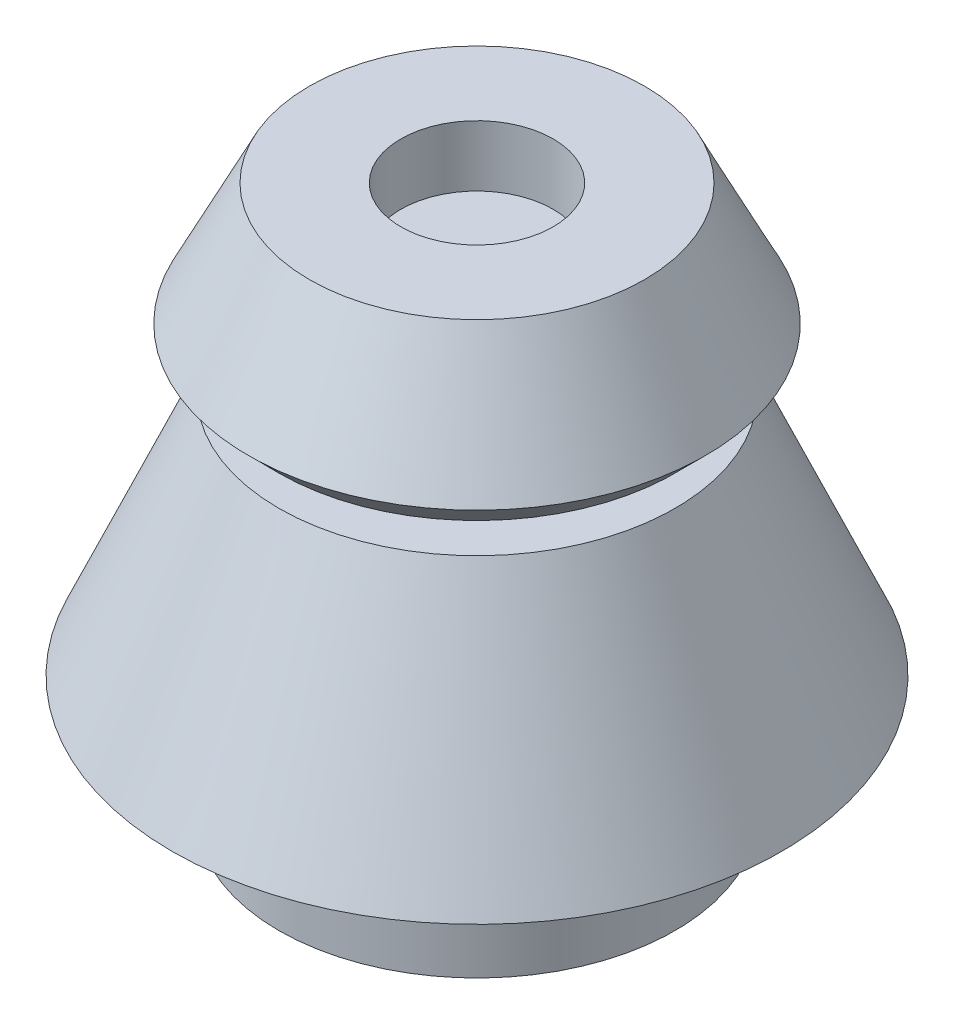
SolidWorks part; units mm, degrees
ref_plane "Front Plane" through (0, 0, 0) normal (0, 0, 1) x (1, 0, 0)
ref_plane "Top Plane" through (0, 0, 0) normal (0, 1, 0) x (1, 0, 0)
ref_plane "Right Plane" through (0, 0, 0) normal (1, 0, 0) x (0, 0, -1)
sketch "Sketch1" plane through (0, 0, 0) normal (0, 0, 1) x (1, 0, 0)
  line L0 (0, 0) -> (0, 28250.8537) construction
  line L1 (0, 0) -> (-2.5, 0)
  line L2 (-2.5, 0) -> (-2.5, 2)
  line L3 (-2.5, 2) -> (-5.5, 2)
  line L4 (-5.5, 2) -> (-7.5, -2)
  line L5 (-7.5, -2) -> (-6.5, -3)
  line L6 (-6.5, -3) -> (-1.5, -3)
  line L7 (-1.5, -3) -> (-1.5, -4)
  line L8 (-1.5, -4) -> (-6.5, -4)
  line L9 (-6.5, -4) -> (-10, -12)
  line L10 (-10, -12) -> (-6.5, -12)
  line L11 (-6.5, -12) -> (-6.5, -16)
  line L12 (-6.5, -16) -> (0, -16)
  line L13 (0, -16) -> (0, 0)
  dimension "D1" = 13
  dimension "D2" = 4
  dimension "D3" = 11
  dimension "D4" = 5
  dimension "D5" = 14
  dimension "D6" = 20
  dimension "D7" = 8
  dimension "D8" = 13
  dimension "D9" = 1
  dimension "D10" = 3
  dimension "D11" = 13
  dimension "D12" = 1
  dimension "D13" = 2
  dimension "D14" = 1
revolve "Revolve1" add sketch "Sketch1" angle 360 about L0
